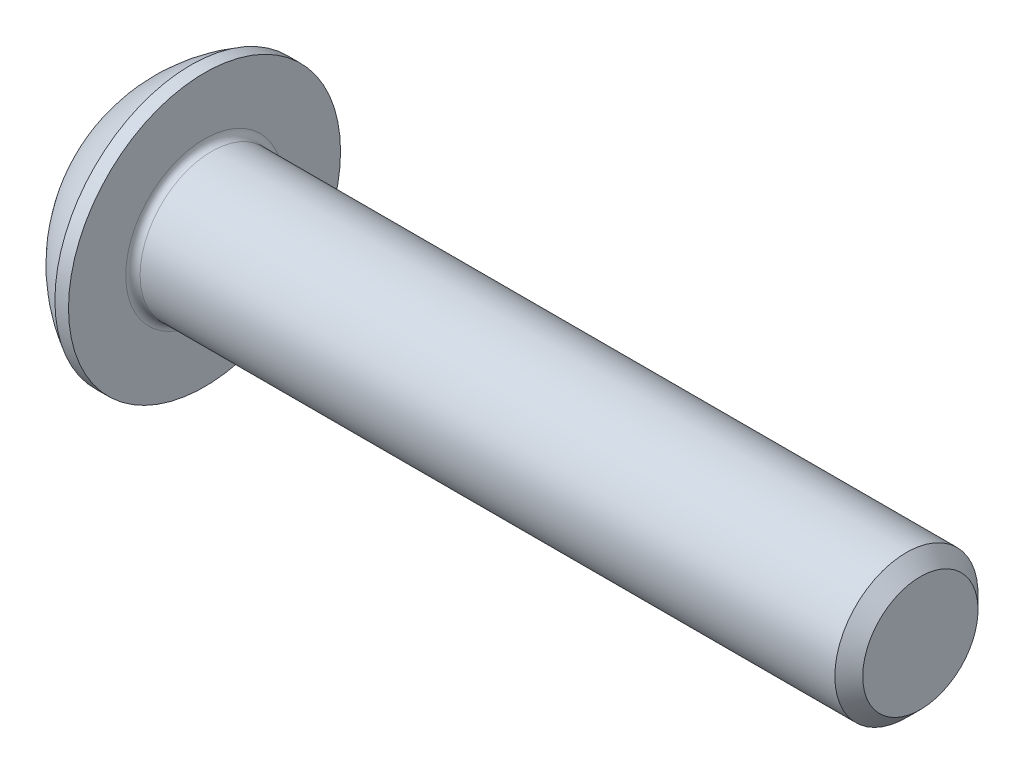
SolidWorks part; units mm, degrees
ref_plane "Plane1" through (0, 0, 0) normal (0, 0, 1) x (1, 0, 0)
ref_plane "Plane2" through (0, 0, 0) normal (0, 1, 0) x (1, 0, 0)
ref_plane "Plane3" through (0, 0, 0) normal (1, 0, 0) x (0, 0, -1)
sketch "BodySke" plane through (0, 0, 0) normal (0, 0, 1) x (1, 0, 0)
  line L0 (22.2, 0) -> (22.2, 1.61)
  line L1 (21.81, 2) -> (2.2, 2)
  line L2 (2.2, 2) -> (2.2, 3.8)
  line L3 (2.2, 3.8) -> (1.82, 3.8)
  line L4 (0, 0) -> (101.6, 0) construction
  line L5 (2.2, -3.8) -> (1.82, -3.8) construction
  line L6 (55.6768, -2) -> (2.2, -2) construction
  line L7 (22.2, 0) -> (0, 0)
  line L8 (0, 1.9) -> (0, -1.9) construction
  line L9 (0, 0) -> (0, 1.9)
  line L10 (22.2, 1.61) -> (21.81, 2)
  line L11 (22.2, -1.61) -> (21.81, -2) construction
  line L12 (2.9, 9.525) -> (2.9, -2) construction
  line L13 (2.2, 9.525) -> (2.2, -2) construction
  arc A1 (0, 1.9) -> (1.82, 3.8) centre (3.8853, 0) cw
  dimension "Diameter" = 4
  dimension "Head_dia" = 7.6
  dimension "D1" = 3.8
  dimension "Head_ht" = 2.2
  dimension "Head_side_ht" = 0.38
  dimension "Minor_dia" = 3.22
  dimension "Body_ch_ang" = 45
  dimension "Advance" = 0.7
revolve "BaseBody" add sketch "BodySke" angle 360 about L4
cosmetic thread "ThreadCosmetic" [suppressed] parameters "Thread_length"=18.6, "Thread_minor"=3.22
fillet "Fillet1" radius 0.2 1 edges at (2.2, 0, 2)
sketch "Sketch2" plane through (0, 0, 0) normal (0, 0, 1) x (1, 0, 0)
  line L0 (0, 1.25) -> (1.3, 1.25)
  line L1 (1.3, 1.25) -> (2.0217, 0)
  line L3 (2.0217, 0) -> (0, 0)
  line L4 (0, 0) -> (0, 1.25)
  line L5 (0, -1.25) -> (1.3, -1.25) construction
  line L6 (0, 0) -> (47.625, 0) construction
  dimension "D2" = 60
  dimension "PreBroach_depth" = 1.3
  dimension "PreBroach_dia" = 2.5
revolve "PreBroach" cut sketch "Sketch2" angle 360 about L6
sketch "Sketch3" plane through (0, 0, 0) normal (1, 0, 0) x (0, 0, -1)
  line L0 (-1.25, -0.7217) -> (-1.25, 0.7217)
  line L1 (-1.25, 0.7217) -> (0, 1.4434)
  line L2 (0, 1.4434) -> (1.25, 0.7217)
  line L3 (1.25, 0.7217) -> (1.25, -0.7217)
  line L4 (1.25, -0.7217) -> (0, -1.4434)
  line L5 (0, -1.4434) -> (-1.25, -0.7217)
  dimension "Hex_size" = 2.5
  dimension "D3" = 2.5
  dimension "D1" = 1.25
  dimension "D2" = 1.25
extrude "Hex" cut sketch "Sketch3" along normal blind 1.3
sketch "ThdSchSke" plane through (0, 0, 0) normal (0, 0, 1) x (1, 0, 0)
  line L0 (3.6, -1.61) -> (3.3269, -2)
  line L1 (3.6, -1.61) -> (3.8731, -2)
  line L2 (3.8731, -2) -> (3.8731, -2.5)
  line L3 (-3.175, 0) -> (5.1513, 0) construction
  line L5 (3.8731, -2.5) -> (3.3269, -2.5)
  line L6 (3.3269, -2.5) -> (3.3269, -2)
  dimension "Diameter" = 4
  dimension "Thread_minor" = 3.22
  dimension "SideAngle" = 55
  dimension "VeeAngle" = 70
  dimension "Overcut" = 5
  dimension "Start" = 3.6
revolve "ThreadSchematic" [suppressed] cut sketch "ThdSchSke" angle 360 about L3
pattern_linear "ThdSchPat" [suppressed]
equation "\"D1@BodySke\" = \"Head_dia@BodySke\" * .5"
equation "\"Thread_minor@ThreadCosmetic\" = \"Minor_dia@BodySke\""
equation "\"D1@Sketch3\" = \"Hex_size@Sketch3\" / 2"
equation "\"D2@Sketch3\" = \"D1@Sketch3\""
equation "\"D3@Sketch3\" = \"Hex_size@Sketch3\""
equation "\"Thread_length@ThreadCosmetic\" = ((sgn( (\"Length@BodySke\" - \"Advance@BodySke\" * 2.0) - \"Thread_nom@BodySke\" )-1)*( (\"Length@BodySke\" - \"Advance@BodySke\" * 2.0) - \"Thread_nom@BodySke\" ))/-2+ \"Thread_nom@BodySke\""
equation "\"Thread_minor@ThdSchSke\" = \"Minor_dia@BodySke\""
equation "\"Diameter@ThdSchSke\" = \"Diameter@BodySke\""
equation "\"Overcut@ThdSchSke\" = \"Diameter@BodySke\" * 1.25"
equation "\"Start@ThdSchSke\" = \"Head_ht@BodySke\" + \"Length@BodySke\" - \"Thread_length@ThreadCosmetic\"  '---Non-countersunk---"
equation "\"Num_threads@ThdSchPat\" = int( \"Thread_length@ThreadCosmetic\" / \"Advance@BodySke\" + 0.999 )  + 1"
equation "\"Advance@ThdSchPat\" = \"Thread_length@ThreadCosmetic\" /  (\"Num_threads@ThdSchPat\" - 1) 'relax it"
equation "\"Num_threads@ThdSchPat\" = \"Num_threads@ThdSchPat\" - sgn( \"Num_threads@ThdSchPat\" - 1) '---chamfered tips only---"
